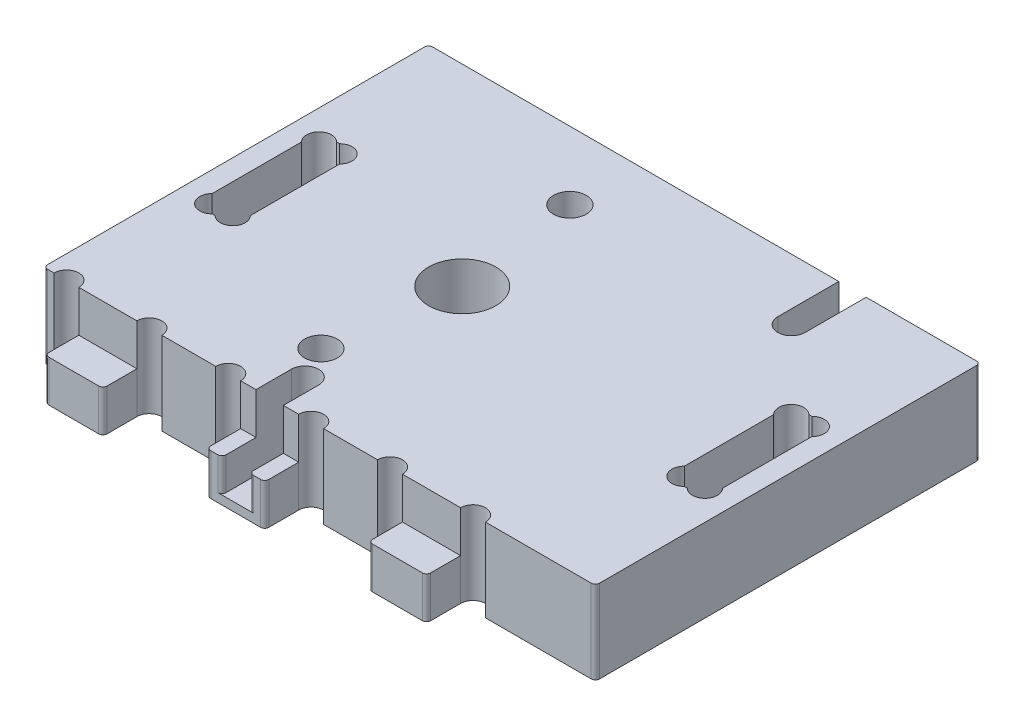
SolidWorks part; units mm, degrees
material "POM Acetal Copolymer"
ref_plane "Front Plane" through (0, 0, 0) normal (0, 0, 1) x (1, 0, 0)
ref_plane "Top Plane" through (0, 0, 0) normal (0, 1, 0) x (1, 0, 0)
ref_plane "Right Plane" through (0, 0, 0) normal (1, 0, 0) x (0, 0, -1)
sketch "Sketch1" plane through (0, 0, 0) normal (0, 1, 0) x (1, 0, 0)
  line L0 (23, 23.2) -> (23, -27.3) construction
  line L1 (-23, 23.2) -> (-23, -27.3) construction
  line L2 (-23, 23.2) -> (23, 23.2)
  line L3 (23, -27.3) -> (16, -27.3)
  line L4 (-3.5, -23.2) -> (-3.5, -27.3)
  line L5 (16, -27.3) -> (16, -23.2)
  line L6 (-3.5, -27.3) -> (3.5, -27.3)
  line L7 (3.5, -27.3) -> (3.5, -23.2)
  line L8 (-23, -27.3) -> (-16, -27.3)
  line L9 (-3.5, -23.2) -> (-16, -23.2)
  line L10 (-16, -27.3) -> (-16, -23.2)
  line L11 (16, -23.2) -> (3.5, -23.2)
  line L12 (23, 23.2) -> (39.25, 23.2)
  line L13 (0, 23.2) -> (0, -23.2) construction
  line L14 (39.25, 23.2) -> (39.25, -23.2)
  line L15 (23, -27.3) -> (23, -23.2)
  line L16 (23, -23.2) -> (39.25, -23.2)
  line L17 (-23, -23.2) -> (-23, -27.3)
  line L18 (23, 0) -> (-23, 0) construction
  line L19 (-27.25, -23.2) -> (-27.25, 23.2)
  line L20 (-27.25, 23.2) -> (-23, 23.2)
  line L21 (-23, -23.2) -> (-27.25, -23.2)
  dimension "D1" = 46
  dimension "D3" = 50.5
  dimension "D4" = 7
  dimension "D5" = 16.25
  dimension "D8" = 66.5
  dimension "D2" = 46.4
  dimension "D6" = 4.25
  dimension "D7" = 32
  dimension "D9" = 4.1
extrude "Boss-Extrude1" add sketch "Sketch1" along normal blind 10
sketch "Sketch2" plane through (0, 10, 0) normal (0, 1, 0) x (1, 0, 0)
  line L0 (-4, 15) -> (-4, -15) construction
  line L1 (-1000, 0) -> (49000, 0) construction
  line L3 (0, -1000) -> (0, 49000) construction
  circle A0 centre (0, 0) radius 4.05
  circle A1 centre (-2.025, 15) radius 1.975
  circle A2 centre (0, 0) radius 4 construction
  circle A4 centre (-2.025, -15) radius 1.975
  dimension "D3" = 8.1
  dimension "D4" = 8
  dimension "D1" = 3.95
  dimension "D2" = 30
extrude "Cut-Extrude1" cut sketch "Sketch2" against normal through all
sketch "Sketch14" plane through (0, 10, 0) normal (0, 1, 0) x (1, 0, 0)
  line L0 (23, -27.3) -> (23, -23.2) construction
  line L1 (-27.25, -23.2) -> (23, -23.2)
  line L2 (-27.25, -23.2) -> (-27.25, -27.3)
  line L3 (-27.25, -27.3) -> (23, -27.3)
  line L4 (23, -23.2) -> (23, -27.3)
  line L5 (16, -27.3) -> (23, -27.3) construction
  line L6 (-16, -23.2) -> (-3.5, -23.2) construction
  line L9 (-27.25, 23.2) -> (-27.25, -23.2) construction
extrude "Cut-Extrude13" cut sketch "Sketch14" against normal blind 5
sketch "Sketch16" plane through (0, 0, 0) normal (0, -1, 0) x (1, 0, 0)
  line L0 (39.25, 0) -> (-27.25, 0) construction
  line L1 (32.15, -7.5) -> (36.75, -7.5)
  line L2 (32.15, -7.5) -> (32.15, 7.5)
  line L3 (32.15, 7.5) -> (36.75, 7.5)
  line L4 (36.75, -7.5) -> (36.75, 7.5)
  line L5 (39.25, 23.2) -> (39.25, -23.2) construction
  line L6 (39.25, 23.2) -> (39.25, -23.2) construction
  line L7 (-27.25, -23.2) -> (-27.25, 23.2) construction
  line L8 (-20.15, 7.5) -> (-24.75, 7.5)
  line L9 (-20.15, 7.5) -> (-20.15, -7.5)
  line L10 (-20.15, -7.5) -> (-24.75, -7.5)
  line L11 (-24.75, 7.5) -> (-24.75, -7.5)
  circle A0 centre (-2.025, -15) radius 1.975 construction
  dimension "D7" = 15
  dimension "D1" = 4.6
  dimension "D3" = 15
  dimension "D4" = 4.6
  dimension "D5" = 2.5
  dimension "D6" = 52.3
  dimension "D8" = 18.125
  dimension "D9" = 2.5
extrude "Cut-Extrude15" cut sketch "Sketch16" against normal blind 10
sketch "Sketch15" plane through (0, 10, 0) normal (0, 1, 0) x (1, 0, 0)
  line L0 (14.5, -27.3) -> (14.5, -23.2) construction
  line L1 (0, -0.0347) -> (0, 23.2) construction
  line L2 (13, -27.3) -> (13, -23.2)
  line L3 (16, -27.3) -> (16, -23.2)
  line L4 (32.15, 6.4393) -> (33.2107, 6.4393) construction
  line L6 (33.2107, 6.4393) -> (33.2107, 7.5) construction
  line L7 (-27.25, -23.2) -> (39.25, -23.2) construction
  line L8 (32.15, 7.5) -> (36.75, 7.5) construction
  line L9 (5, -27.3) -> (5, -23.2) construction
  line L10 (0, -23.2) -> (0, -0.0347) construction
  line L11 (3.5, -27.3) -> (3.5, -23.2)
  line L12 (6.5, -27.3) -> (6.5, -23.2)
  line L13 (34.45, 7.5) -> (34.45, -7.5) construction
  line L14 (36.75, -7.5) -> (32.15, -7.5) construction
  line L15 (-14.5, -27.3) -> (-14.5, -23.2) construction
  line L16 (-13, -27.3) -> (-13, -23.2)
  line L17 (-16, -27.3) -> (-16, -23.2)
  line L18 (-5, -27.3) -> (-5, -23.2) construction
  line L19 (-3.5, -27.3) -> (-3.5, -23.2)
  line L20 (-6.5, -27.3) -> (-6.5, -23.2)
  line L21 (-27.25, -23.2) -> (39.25, -23.2) construction
  line L22 (-16, -27.3) -> (-16, -23.2) construction
  line L23 (6, 23.2) -> (6, 11.0524) construction
  line L24 (39.25, 23.2) -> (-27.25, 23.2) construction
  line L27 (-27.25, -23.2) -> (39.25, -23.2) construction
  line L28 (39.25, 23.2) -> (-27.25, 23.2) construction
  line L29 (24.5, -27.3) -> (24.5, -23.2) construction
  line L30 (23, -27.3) -> (23, -23.2)
  line L31 (26, -27.3) -> (26, -23.2)
  line L32 (23, -27.3) -> (23, -23.2) construction
  line L33 (16, -23.2) -> (16, -27.3) construction
  line L34 (-27.25, -23.2) -> (39.25, -23.2) construction
  line L35 (-27.25, -23.2) -> (39.25, -23.2) construction
  line L36 (32.15, 0) -> (36.75, 0) construction
  line L37 (32.15, -7.5) -> (32.15, 7.5) construction
  line L38 (36.75, 7.5) -> (36.75, -7.5) construction
  line L48 (-20.15, 7.5) -> (-20.15, -7.5) construction
  line L49 (-24.75, -7.5) -> (-24.75, 7.5) construction
  line L53 (-20.15, 0) -> (-24.75, 0) construction
  line L57 (-24.5, -27.3) -> (-24.5, -23.2) construction
  line L58 (-23, -27.3) -> (-23, -23.2)
  line L59 (-26, -27.3) -> (-26, -23.2)
  arc A0 (13, -27.3) -> (16, -27.3) centre (14.5, -27.3) ccw
  arc A1 (16, -23.2) -> (13, -23.2) centre (14.5, -23.2) ccw
  arc A2 (3.5, -27.3) -> (6.5, -27.3) centre (5, -27.3) ccw
  arc A3 (6.5, -23.2) -> (3.5, -23.2) centre (5, -23.2) ccw
  arc A4 (-13, -27.3) -> (-16, -27.3) centre (-14.5, -27.3) cw
  arc A5 (-16, -23.2) -> (-13, -23.2) centre (-14.5, -23.2) cw
  arc A6 (-3.5, -27.3) -> (-6.5, -27.3) centre (-5, -27.3) cw
  arc A7 (-6.5, -23.2) -> (-3.5, -23.2) centre (-5, -23.2) cw
  arc A8 (34.45, 7.2843) -> (34.45, 5.5943) centre (33.2107, 6.4393) ccw
  arc A9 (34.45, 7.2843) -> (34.45, 5.5943) centre (35.6893, 6.4393) cw
  arc A10 (34.45, -7.2843) -> (34.45, -5.5943) centre (33.2107, -6.4393) cw
  arc A11 (34.45, -7.2843) -> (34.45, -5.5943) centre (35.6893, -6.4393) ccw
  arc A12 (23, -27.3) -> (26, -27.3) centre (24.5, -27.3) ccw
  arc A13 (26, -23.2) -> (23, -23.2) centre (24.5, -23.2) ccw
  arc A14 (-22.45, -7.2843) -> (-22.45, -5.5943) centre (-21.2107, -6.4393) ccw
  arc A15 (-22.45, -7.2843) -> (-22.45, -5.5943) centre (-23.6893, -6.4393) cw
  arc A16 (-22.45, 7.2843) -> (-22.45, 5.5943) centre (-23.6893, 6.4393) ccw
  arc A17 (-22.45, 7.2843) -> (-22.45, 5.5943) centre (-21.2107, 6.4393) cw
  arc A22 (-23, -27.3) -> (-26, -27.3) centre (-24.5, -27.3) cw
  arc A23 (-26, -23.2) -> (-23, -23.2) centre (-24.5, -23.2) cw
  point P4 (14.5, -25.25)
  point P17 (5, -25.25)
  point P28 (-14.5, -25.25)
  point P35 (-5, -25.25)
  point P67 (24.5, -25.25)
  point P125 (-24.5, -25.25)
  dimension "D2" = 3
  dimension "D1" = 3
  dimension "D5" = 3
extrude "Cut-Extrude14" cut sketch "Sketch15" against normal through all
sketch "Sketch19" plane through (0, 0, -23.2) normal (0, 0, -1) x (-1, 0, 0)
  line L0 (-39.25, 0) -> (27.25, 0) construction
  line L1 (-20.33, 0) -> (-27.33, 0)
  line L2 (-20.33, 0) -> (-20.33, 5)
  line L3 (-20.33, 5) -> (-27.33, 5)
  line L4 (-27.33, 0) -> (-27.33, 5)
  line L5 (-23.83, 0) -> (-23.83, 2.867) construction
  dimension "D1" = 23.83
  dimension "D2" = 7
  dimension "D3" = 5
extrude "Boss-Extrude2" add sketch "Sketch19" along normal blind 1
sketch "Sketch17" plane through (0, 10, 0) normal (0, 1, 0) x (1, 0, 0)
  line L0 (23.83, 24.2) -> (23.83, 15.85) construction
  line L1 (25.48, 24.2) -> (25.48, 15.85)
  line L2 (22.18, 24.2) -> (22.18, 15.85)
  line L4 (0, 0) -> (0, 11.1143) construction
  line L7 (20.33, 24.2) -> (27.33, 24.2) construction
  line L8 (0, -18.95) -> (0, -27.3) construction
  line L9 (1.65, -18.95) -> (1.65, -27.3)
  line L10 (-1.65, -18.95) -> (-1.65, -27.3)
  line L11 (-3.5, -27.3) -> (3.5, -27.3) construction
  arc A0 (25.48, 24.2) -> (22.18, 24.2) centre (23.83, 24.2) ccw
  arc A1 (22.18, 15.85) -> (25.48, 15.85) centre (23.83, 15.85) ccw
  arc A2 (1.65, -18.95) -> (-1.65, -18.95) centre (0, -18.95) ccw
  arc A3 (-1.65, -27.3) -> (1.65, -27.3) centre (0, -27.3) ccw
  point P2 (23.83, 20.025)
  point P14 (0, -23.125)
  dimension "D4" = 1.65
  dimension "D1" = 3.3
  dimension "D2" = 8.35
  dimension "D3" = 23.83
  dimension "D5" = 8.35
extrude "Cut-Extrude16" cut sketch "Sketch17" against normal blind 8.95
fillet "Fillet1" radius 0.5 19 edges at (-27.25, 5, 23.2) (-27.25, 5, -23.2) (39.25, 5, -23.2) (39.25, 5, 23.2) (20.33, 2.5, -24.2) (27.33, 2.5, -24.2) (25.48, 3.025, -24.2) (22.18, 3.025, -24.2) (-1.65, 3.025, 27.3) (1.65, 3.025, 27.3) (-16, 2.5, 27.3) (-23, 2.5, 27.3) (23, 2.5, 27.3) (16, 2.5, 27.3) (3.5, 2.5, 27.3) (-3.5, 2.5, 27.3)
